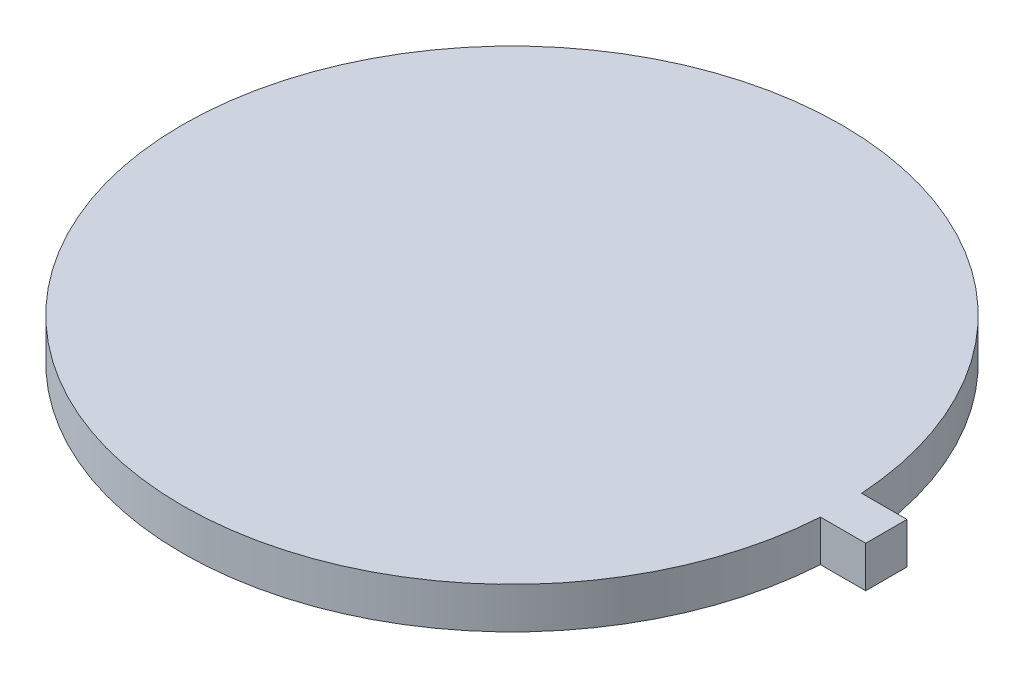
SolidWorks part; units mm, degrees
material "ABS"
ref_plane "Front Plane" through (0, 0, 0) normal (0, 0, 1) x (1, 0, 0)
ref_plane "Top Plane" through (0, 0, 0) normal (0, 1, 0) x (1, 0, 0)
ref_plane "Right Plane" through (0, 0, 0) normal (1, 0, 0) x (0, 0, -1)
other "Bounding Box"
ref_plane "Default Plane" through (-21.4445, 12.7, -142.0748) normal (-0.5937, 0, 0.8047) x (0.8047, 0, 0.5937)
sketch "Sketch1" plane through (0, 0, 0) normal (0, 1, 0) x (1, 0, 0)
  line L1 (115.3714, -3.175) -> (115.3714, 6.35)
  line L2 (115.3714, -3.175) -> (115.3714, -6.35)
  line L3 (115.3714, 6.35) -> (101.4014, 6.35)
  line L4 (115.3714, -6.35) -> (101.4014, -6.35)
  arc A1 (101.4014, 6.35) -> (101.4014, -6.35) centre (0, 0) ccw
  dimension "D2" = 203.2
  dimension "D3" = 12.7
  dimension "D4" = 13.97
  dimension "D5" = 13.97
extrude "Boss-Extrude2" add sketch "Sketch1" along normal blind 12.7
